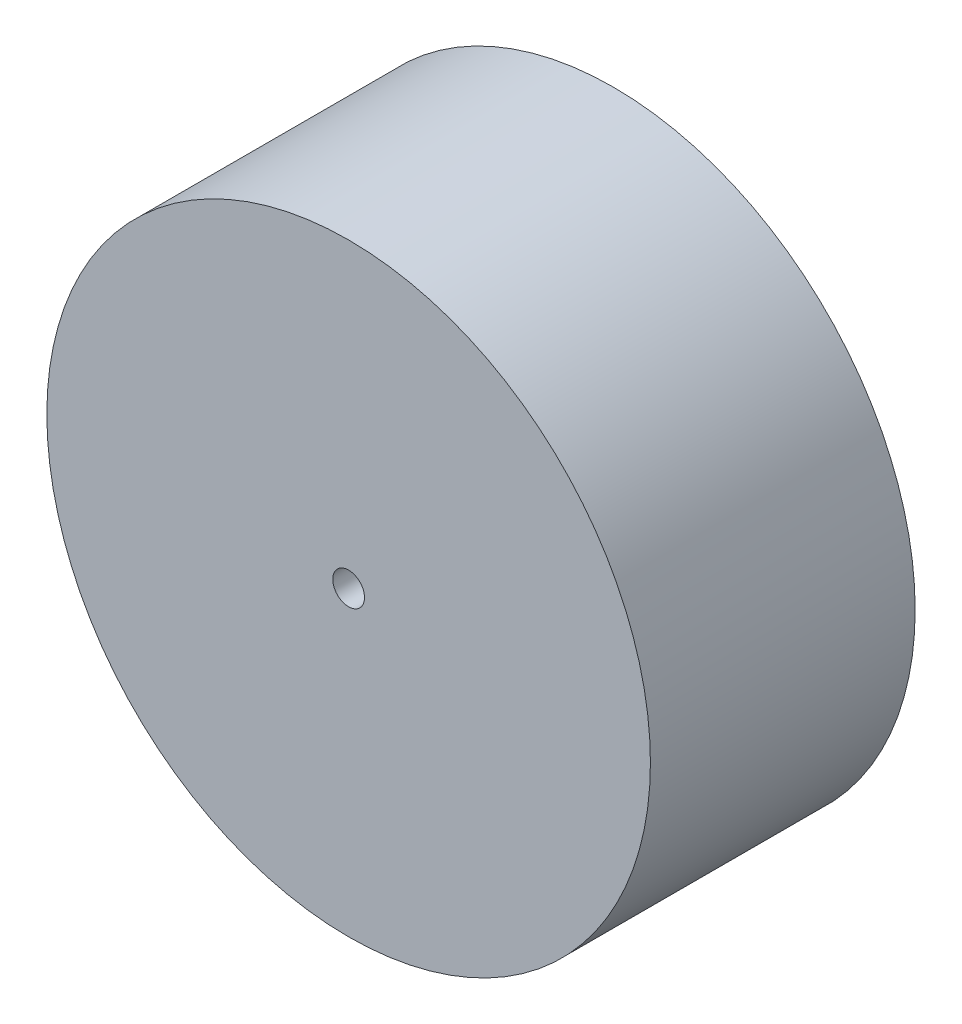
SolidWorks part; units mm, degrees
ref_plane "Спереди" through (0, 0, 0) normal (0, 0, 1) x (1, 0, 0)
ref_plane "Сверху" through (0, 0, 0) normal (0, 1, 0) x (1, 0, 0)
ref_plane "Справа" through (0, 0, 0) normal (1, 0, 0) x (0, 0, -1)
other "Configuration Table"
sketch "Эскиз1" plane through (0, 0, 0) normal (0, 0, 1) x (1, 0, 0)
  circle A0 centre (0, 0) radius 28.5
  circle A1 centre (0, 0) radius 1.5
  dimension "D1" = 57
  dimension "D2" = 3
extrude "Бобышка-Вытянуть1" add sketch "Эскиз1" along normal blind 25
